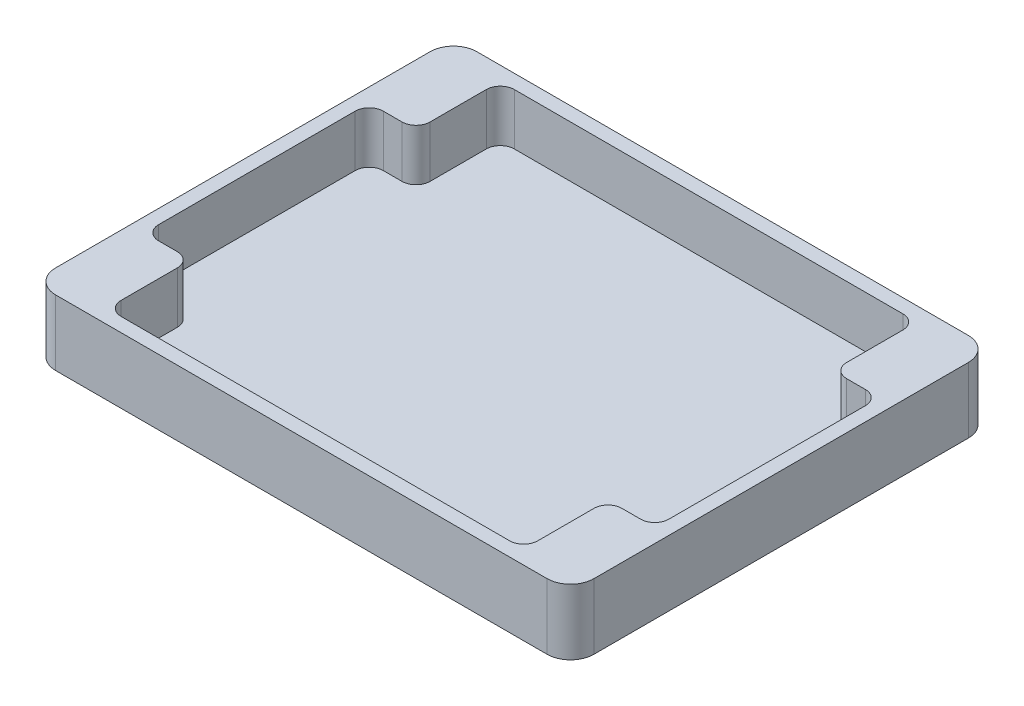
SolidWorks part; units mm, degrees
material "ABS"
ref_plane "Front Plane" through (0, 0, 0) normal (0, 0, 1) x (1, 0, 0)
ref_plane "Top Plane" through (0, 0, 0) normal (0, 1, 0) x (1, 0, 0)
ref_plane "Right Plane" through (0, 0, 0) normal (1, 0, 0) x (0, 0, -1)
sketch "Sketch1" plane through (0, 0, 0) normal (0, 1, 0) x (1, 0, 0)
  line L1 (0, 0) -> (115, 0)
  line L2 (0, 0) -> (0, 90)
  line L3 (0, 90) -> (115, 90)
  line L4 (115, 0) -> (115, 90)
  dimension "D1" = 115
  dimension "D2" = 90
extrude "Boss-Extrude1" add sketch "Sketch1" along normal blind 14
sketch "Sketch3" plane through (0, 14, 0) normal (0, 1, 0) x (1, 0, 0)
  line L14 (112, 3) -> (112, 87)
  line L15 (3, 3) -> (112, 3)
  line L16 (3, 87) -> (3, 3)
  line L17 (112, 87) -> (3, 87)
  line L18 (112, 3) -> (112, 87)
  line L19 (3, 3) -> (112, 3)
  line L20 (3, 87) -> (3, 3)
  line L21 (112, 87) -> (3, 87)
  dimension "D1" = 3
extrude "Cut-Extrude1" cut sketch "Sketch3" against normal offset from surface (11 mm away) 3 up to face at (57.5, 0, -45)
sketch "Sketch4" plane through (0, 3, 0) normal (0, 1, 0) x (1, 0, 0)
  line L0 (57.5, 87) -> (57.5, 3) construction
  line L1 (3, 87) -> (13, 87)
  line L2 (3, 87) -> (3, 69)
  line L3 (3, 69) -> (13, 69)
  line L4 (13, 87) -> (13, 69)
  line L5 (112, 87) -> (3, 87) construction
  line L6 (3, 3) -> (112, 3) construction
  line L7 (3, 45) -> (112, 45) construction
  line L8 (3, 87) -> (3, 3) construction
  line L9 (112, 3) -> (112, 87) construction
  line L10 (112, 69) -> (102, 69)
  line L11 (102, 87) -> (102, 69)
  line L12 (112, 87) -> (102, 87)
  line L13 (112, 87) -> (112, 69)
  line L14 (112, 3) -> (112, 21)
  line L15 (112, 3) -> (102, 3)
  line L16 (102, 3) -> (102, 21)
  line L17 (112, 21) -> (102, 21)
  line L18 (3, 21) -> (13, 21)
  line L19 (13, 3) -> (13, 21)
  line L20 (3, 3) -> (13, 3)
  line L21 (3, 3) -> (3, 21)
  dimension "D1" = 10
  dimension "D2" = 18
extrude "Boss-Extrude2" add sketch "Sketch4" along normal up to surface (11 mm away) up to face at (57.5, 14, -45)
fillet "Fillet1" radius 3 12 edges at (112, 8.5, -21) (102, 8.5, -21) (102, 8.5, -3) (13, 8.5, -3) (3, 8.5, -21) (13, 8.5, -21) (112, 8.5, -69) (102, 8.5, -69) (102, 8.5, -87) (13, 8.5, -87) (3, 8.5, -69) (13, 8.5, -69)
fillet "Fillet2" radius 5 4 edges at (115, 7, 0) (0, 7, 0) (115, 7, -90) (0, 7, -90)
